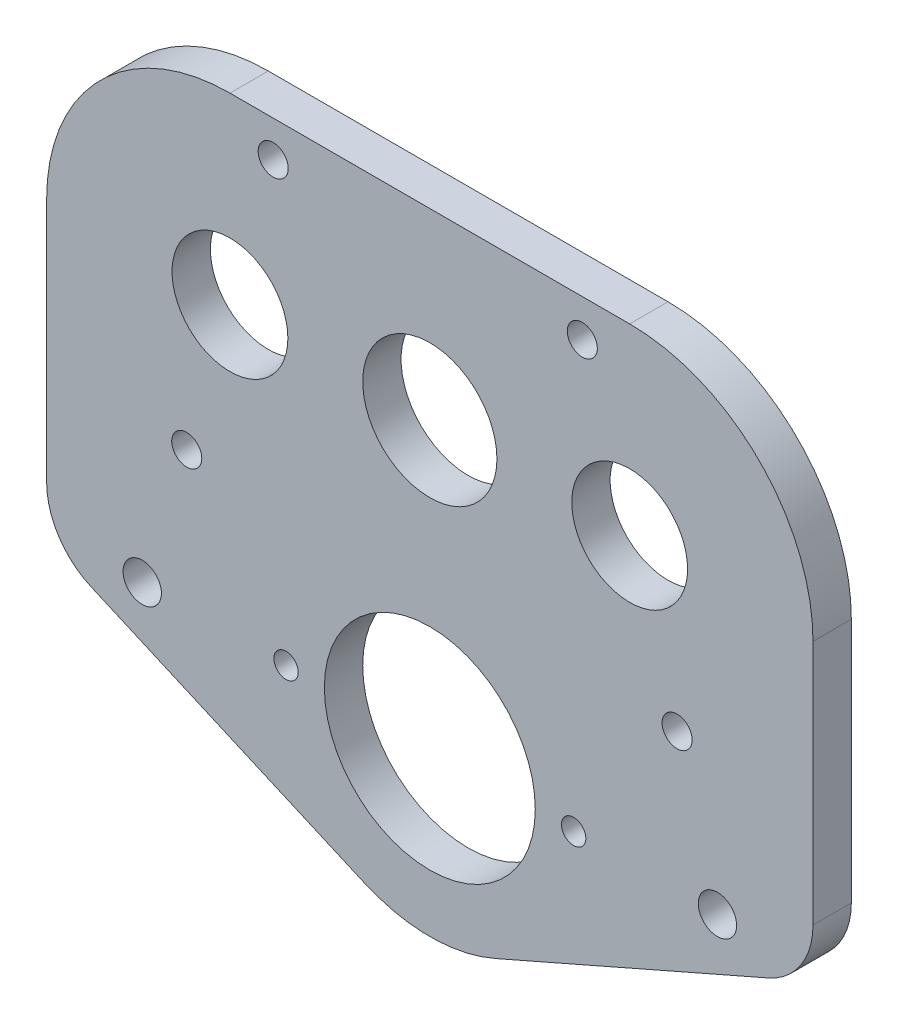
SolidWorks part; units mm, degrees
ref_plane "Front Plane" through (0, 0, 0) normal (0, 0, 1) x (1, 0, 0)
ref_plane "Top Plane" through (0, 0, 0) normal (0, 1, 0) x (1, 0, 0)
ref_plane "Right Plane" through (0, 0, 0) normal (1, 0, 0) x (0, 0, -1)
sketch "Sketch1" plane through (0, 0, 0) normal (0, 0, 1) x (1, 0, 0)
  line L0 (-73.025, -38.1) -> (-73.025, 38.1) construction
  line L1 (-327.025, 38.1) -> (327.025, 38.1) construction
  line L2 (-327.025, 38.1) -> (-327.025, -38.1) construction
  line L3 (-327.025, -38.1) -> (327.025, -38.1) construction
  line L4 (327.025, 38.1) -> (327.025, -38.1) construction
  line L5 (-327.025, 38.1) -> (327.025, -38.1) construction
  line L6 (-327.025, -38.1) -> (327.025, 38.1) construction
  line L7 (-33.0962, 72.4662) -> (-33.0962, 21.6662) construction
  line L8 (-63.4492, 47.0662) -> (-63.4492, 6.3877)
  line L9 (-56.0792, -4.8888) -> (-10.8326, -24.718)
  line L10 (63.4492, 47.0662) -> (63.4492, 6.3875)
  line L11 (56.0792, -4.8891) -> (10.8325, -24.7181)
  line L13 (-33.0962, 77.4192) -> (33.0962, 77.4192)
  line L15 (25.2472, 71.223) -> (40.9452, 22.9094) construction
  line L17 (-40.2522, 22.6951) -> (-25.9402, 71.4373) construction
  circle A0 centre (0, 0) radius 17.4625
  circle A1 centre (0, 0) radius 63.5 construction
  circle A2 centre (47.625, 0) radius 3.175
  circle A3 centre (-23.8125, 0) radius 2.0193
  circle A4 centre (-47.625, 0) radius 3.175
  circle A5 centre (23.8125, 0) radius 2.0193
  circle A6 centre (0, 47.0662) radius 11.1125
  circle A7 centre (33.0962, 47.0662) radius 9.5885
  circle A8 centre (-33.0962, 47.0662) radius 9.5885
  circle A9 centre (-33.0962, 47.0662) radius 30.353 construction
  circle A10 centre (33.0962, 47.0662) radius 30.353 construction
  circle A11 centre (0, 0) radius 26.9875 construction
  circle A12 centre (-47.625, 0) radius 6.35 construction
  circle A13 centre (-33.0962, 21.6662) radius 2.4892 construction
  circle A14 centre (-33.0962, 72.4662) radius 2.4892 construction
  circle A15 centre (33.0962, 21.6662) radius 2.4892 construction
  circle A16 centre (33.0962, 72.4662) radius 2.4892 construction
  circle A17 centre (-25.9402, 71.4373) radius 2.4892
  circle A18 centre (-6.5231, 51.5099) radius 2.4892 [skipped]
  circle A19 centre (-4.4672, 34.1129) radius 2.4892 [skipped]
  circle A20 centre (-11.3852, 18.0188) radius 2.4892 [skipped]
  circle A21 centre (-25.4235, 7.5398) radius 2.4892 [skipped]
  circle A22 centre (-42.8205, 5.4839) radius 2.4892 construction
  circle A23 centre (-19.3639, 68.434) radius 2.4892 construction
  circle A24 centre (-69.3936, 26.4402) radius 2.4892 [skipped]
  circle A25 centre (-71.4495, 43.8372) radius 2.4892 [skipped]
  circle A26 centre (-64.5314, 59.9314) radius 2.4892 [skipped]
  circle A27 centre (-50.4932, 70.4103) radius 2.4892 [skipped]
  circle A28 centre (50.4932, 70.4103) radius 2.4892 [skipped]
  circle A29 centre (64.5314, 59.9314) radius 2.4892 [skipped]
  circle A30 centre (71.4495, 43.8372) radius 2.4892 [skipped]
  circle A31 centre (69.3936, 26.4402) radius 2.4892 [skipped]
  circle A32 centre (-13.9002, 63.6997) radius 2.4892 construction
  circle A33 centre (42.8205, 5.4839) radius 2.4892 construction
  circle A34 centre (25.4235, 7.5398) radius 2.4892 [skipped]
  circle A35 centre (11.3852, 18.0188) radius 2.4892 [skipped]
  circle A36 centre (4.4672, 34.1129) radius 2.4892 [skipped]
  circle A37 centre (6.5231, 51.5099) radius 2.4892 [skipped]
  circle A38 centre (-9.9915, 57.6177) radius 2.4892 construction
  circle A39 centre (0, 47.0662) radius 31.75 construction
  arc A40 (-10.8326, -24.718) -> (10.8325, -24.7181) centre (0, 0) ccw
  arc A41 (-33.0962, 77.4192) -> (-63.4492, 47.0662) centre (-33.0962, 47.0662) ccw
  arc A42 (33.0962, 77.4192) -> (63.4492, 47.0662) centre (33.0962, 47.0662) cw
  arc A43 (63.4492, 6.3875) -> (56.0792, -4.8891) centre (51.1373, 6.3875) cw
  arc A44 (-63.4492, 6.3877) -> (-56.0792, -4.8888) centre (-51.1373, 6.3877) ccw
  circle A45 centre (0, 0) radius 39.37 construction
  circle A46 centre (-17.002, 65.5482) radius 2.4892 construction
  circle A47 centre (-58.9146, 12.4019) radius 2.4892 construction
  circle A48 centre (17.002, 65.5482) radius 2.4892 construction
  circle A49 centre (58.9146, 12.4019) radius 2.4892 [skipped]
  circle A50 centre (-7.9547, 50.681) radius 2.4892 construction
  circle A51 centre (-7.9547, 43.4514) radius 2.4892 construction
  circle A52 centre (-9.9915, 36.5147) radius 2.4892 construction
  circle A53 centre (-13.9002, 30.4327) radius 2.4892 construction
  circle A54 centre (-19.3639, 25.6984) radius 2.4892 construction
  circle A55 centre (-25.9402, 22.6951) radius 2.4892 construction
  circle A56 centre (-33.0962, 21.6662) radius 2.4892 construction
  circle A57 centre (-40.2522, 22.6951) radius 2.4892
  circle A58 centre (-46.8285, 25.6984) radius 2.4892 construction
  circle A59 centre (-52.2922, 30.4327) radius 2.4892 construction
  circle A60 centre (-56.2009, 36.5147) radius 2.4892 construction
  circle A61 centre (-58.2377, 43.4514) radius 2.4892 construction
  circle A62 centre (-58.2377, 50.681) radius 2.4892 construction
  circle A63 centre (-56.2009, 57.6177) radius 2.4892 construction
  circle A64 centre (-52.2922, 63.6997) radius 2.4892 construction
  circle A65 centre (-46.8285, 68.434) radius 2.4892 construction
  circle A66 centre (-40.2522, 71.4373) radius 2.4892 construction
  circle A67 centre (40.9452, 71.223) radius 2.4892 construction
  circle A68 centre (48.0259, 67.6152) radius 2.4892 construction
  circle A69 centre (53.6452, 61.9959) radius 2.4892 construction
  circle A70 centre (57.253, 54.9152) radius 2.4892 construction
  circle A71 centre (58.4962, 47.0662) radius 2.4892 construction
  circle A72 centre (57.253, 39.2172) radius 2.4892 construction
  circle A73 centre (53.6452, 32.1365) radius 2.4892 construction
  circle A74 centre (48.0259, 26.5172) radius 2.4892 construction
  circle A75 centre (40.9452, 22.9094) radius 2.4892
  circle A76 centre (33.0962, 21.6662) radius 2.4892 construction
  circle A77 centre (25.2472, 22.9094) radius 2.4892 construction
  circle A78 centre (18.1665, 26.5172) radius 2.4892 construction
  circle A79 centre (12.5472, 32.1365) radius 2.4892 construction
  circle A80 centre (8.9394, 39.2172) radius 2.4892 construction
  circle A81 centre (7.6962, 47.0662) radius 2.4892 construction
  circle A82 centre (8.9394, 54.9152) radius 2.4892 construction
  circle A83 centre (12.5472, 61.9959) radius 2.4892 construction
  circle A84 centre (18.1665, 67.6152) radius 2.4892 construction
  circle A85 centre (25.2472, 71.223) radius 2.4892
  point P24 (-73.025, -38.1)
  point P62 (-37.9583, 38.9751)
  point P85 (37.9583, 38.9751)
  point P150 (-33.0962, 47.0662)
  point P189 (33.0962, 47.0662)
  dimension "D1" = 34.925
  dimension "D2" = 127
  dimension "D3" = 23.8125
  dimension "D7" = 4.0386
  dimension "D8" = 6.35
  dimension "D9" = 22.225
  dimension "D10" = 19.177
  dimension "D11" = 60.706
  dimension "D16" = 12.7
  dimension "D17" = 4.9784
  dimension "D21" = 63.5
  dimension "D22" = 53.975
  dimension "D23" = 126.8984
  dimension "D24" = 127
  dimension "D27" = 78.74
  dimension "D18" = 50.8
  dimension "D4" = 47.625
  dimension "D5" = 47.625
  dimension "D6" = 23.8125
  dimension "D12" = 33.0962
  dimension "D13" = 33.0962
  dimension "D14" = 47.0662
  dimension "D15" = 254
  dimension "D25" = 50.8
  dimension "D26" = 22
  dimension "D19" = 12
  dimension "D20" = 12
  dimension "D29" = 20
extrude "Boss-Extrude1" add sketch "Sketch1" along normal mid plane 6.35
